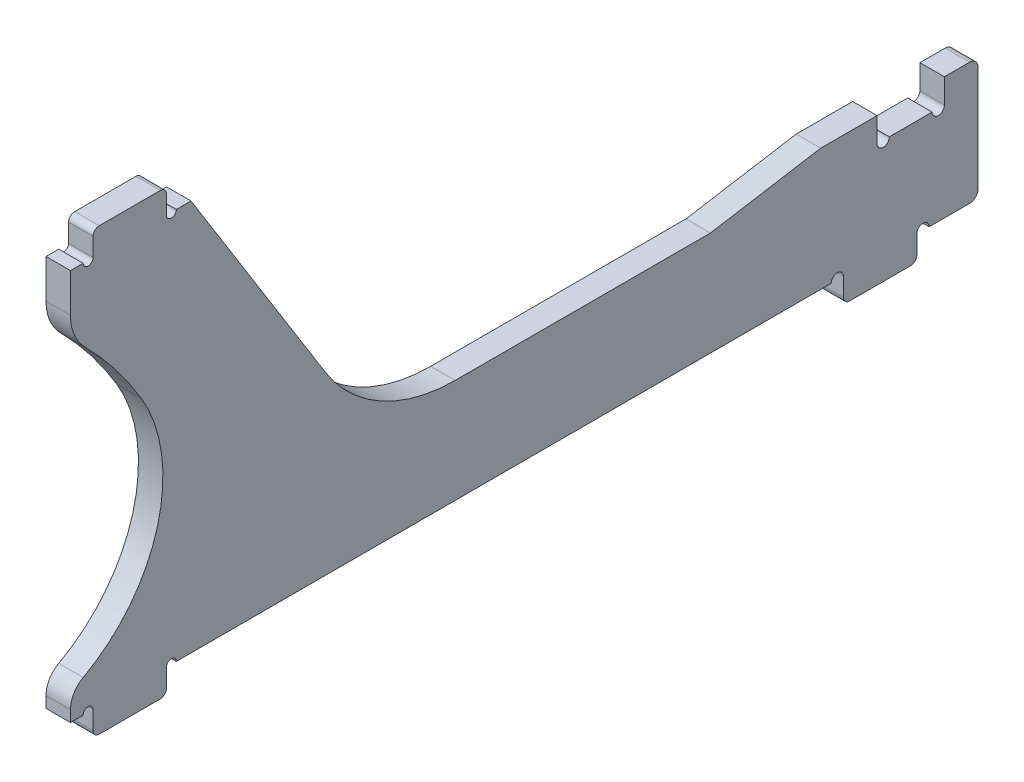
SolidWorks part; units mm, degrees
material "ABS"
ref_plane "Front Plane" through (0, 0, 0) normal (0, 0, 1) x (1, 0, 0)
ref_plane "Top Plane" through (0, 0, 0) normal (0, 1, 0) x (1, 0, 0)
ref_plane "Right Plane" through (0, 0, 0) normal (1, 0, 0) x (0, 0, -1)
sketch "Sketch4" plane through (0, 0, 0) normal (1, 0, 0) x (0, 0, -1)
  line L10 (34.1011, -13.088) -> (34.1011, -4.4622)
  line L11 (33.414, -3.7751) -> (31.3511, -3.7751)
  line L12 (31.3511, -3.7751) -> (31.3511, -5.7751)
  line L13 (30.3511, -5.7751) -> (26.8511, -5.7751)
  line L14 (25.8511, -5.7751) -> (25.8511, -3.7751)
  line L15 (25.8511, -3.7751) -> (21.2337, -3.7751)
  line L16 (21.2337, -3.7751) -> (12.2337, -5.2751)
  line L17 (12.2337, -5.2751) -> (-8.645, -5.2751)
  line L18 (-19.2516, 0.6105) -> (-30.2359, 18.2249)
  line L19 (-30.2359, 18.2249) -> (-31.4347, 18.2249)
  line L20 (-32.2433, 18.2249) -> (-32.2433, 19.7249)
  line L21 (-32.7433, 20.2249) -> (-37.7433, 20.2249)
  line L22 (-38.2433, 19.7249) -> (-38.2433, 18.2249)
  line L23 (-39.052, 18.2249) -> (-40.0905, 18.2249)
  line L24 (-40.0905, 18.2249) -> (-40.0905, 15.063)
  line L25 (-40.0905, -12.8604) -> (-40.0905, -13.7751)
  line L26 (-40.0905, -13.7751) -> (-39.052, -13.7751)
  line L27 (-38.2433, -13.7751) -> (-38.2433, -15.2751)
  line L28 (-37.7433, -15.7751) -> (-32.7433, -15.7751)
  line L29 (-32.2433, -15.2751) -> (-32.2433, -13.7751)
  line L32 (23.1011, -13.7751) -> (23.1011, -15.2751)
  line L34 (29.1011, -15.2751) -> (29.1011, -13.7751)
  line L37 (30.1011, -13.7751) -> (33.414, -13.7751)
  line L38 (28.6011, -15.7751) -> (23.6011, -15.7751)
  line L39 (22.1011, -13.7751) -> (-31.4347, -13.7751)
  line L40 (55, 0) -> (-55, 0) construction
  arc A0 (-38.2433, 18.2249) -> (-39.052, 18.2249) centre (-38.6476, 18.2249) cw
  arc A1 (-38.2433, 19.7249) -> (-37.7433, 20.2249) centre (-37.7433, 19.7249) cw
  arc A2 (-32.7433, 20.2249) -> (-32.2433, 19.7249) centre (-32.7433, 19.7249) cw
  arc A3 (-32.2433, 18.2249) -> (-31.4347, 18.2249) centre (-31.839, 18.2249) ccw
  arc A4 (-19.2516, 0.6105) -> (-8.645, -5.2751) centre (-8.645, 7.2249) ccw
  arc A5 (25.8511, -5.7751) -> (26.8511, -5.7751) centre (26.3511, -5.7751) ccw
  arc A6 (31.3511, -5.7751) -> (30.3511, -5.7751) centre (30.8511, -5.7751) cw
  arc A7 (33.414, -3.7751) -> (34.1011, -4.4622) centre (33.414, -4.4622) cw
  arc A8 (34.1011, -13.088) -> (33.414, -13.7751) centre (33.414, -13.088) cw
  arc A12 (-32.2433, -13.7751) -> (-31.4347, -13.7751) centre (-31.839, -13.7751) cw
  arc A13 (-38.2433, -13.7751) -> (-39.052, -13.7751) centre (-38.6476, -13.7751) ccw
  arc A14 (-40.0905, -12.8604) -> (-39.0479, -11.1044) centre (-38.0905, -12.8604) cw
  arc A15 (-39.0479, -11.1044) -> (-34.2969, 6.2758) centre (-45.0311, -0.1294) ccw
  arc A16 (-34.2969, 6.2758) -> (-38.9288, 12.2444) centre (-60.9608, -9.6348) ccw
  arc A17 (-38.9288, 12.2444) -> (-40.0905, 15.063) centre (-36.0905, 15.063) cw
  arc A18 (-32.7433, -15.7751) -> (-32.2433, -15.2751) centre (-32.7433, -15.2751) ccw
  arc A19 (-37.7433, -15.7751) -> (-38.2433, -15.2751) centre (-37.7433, -15.2751) cw
  arc A20 (29.1011, -13.7751) -> (30.1011, -13.7751) centre (29.6011, -13.7751) cw
  arc A21 (23.1011, -13.7751) -> (22.1011, -13.7751) centre (22.6011, -13.7751) ccw
  arc A22 (23.1011, -15.2751) -> (23.6011, -15.7751) centre (23.6011, -15.2751) ccw
  arc A23 (29.1011, -15.2751) -> (28.6011, -15.7751) centre (28.6011, -15.2751) cw
  point P71 (-35.2433, 20.2249)
  point P72 (28.6011, -5.7751)
  point P73 (-39.5713, 18.2249)
  point P75 (32.3825, -3.7751)
  dimension "D6" = 6
  dimension "D2" = 0.5
  dimension "D8" = 0.5
  dimension "D1" = 63.8444
  dimension "D3" = 6
  dimension "D4" = 2
  dimension "D5" = 2
  dimension "D7" = 32
  dimension "D9" = 2
  dimension "D10" = 8
  dimension "D11" = 5.5
  dimension "D12" = 2.75
  dimension "D13" = 5
  dimension "D14" = 58.052
  dimension "D15" = 53.3527
extrude "Boss-Extrude1" add sketch "Sketch4" along normal blind 2
